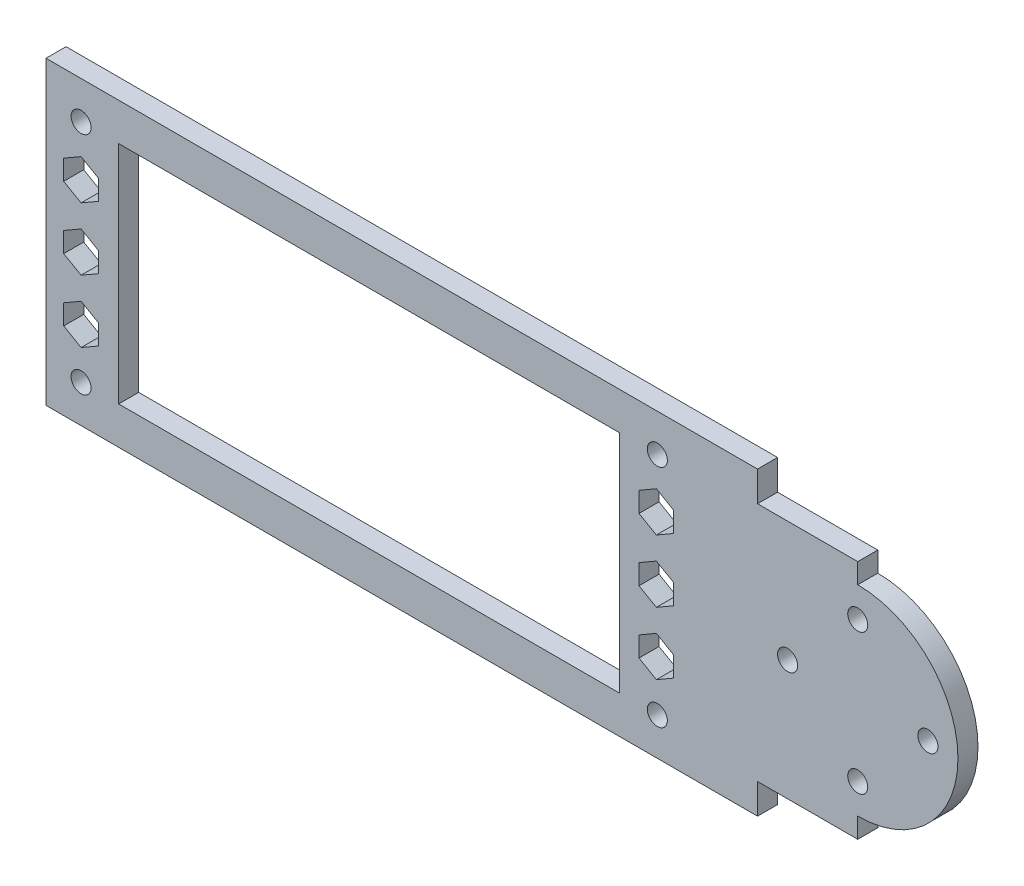
SolidWorks part; units mm, degrees
ref_plane "Front Plane" through (0, 0, 0) normal (0, 0, 1) x (1, 0, 0)
ref_plane "Top Plane" through (0, 0, 0) normal (0, 1, 0) x (1, 0, 0)
ref_plane "Right Plane" through (0, 0, 0) normal (1, 0, 0) x (0, 0, -1)
sketch "Sketch1" plane through (0, 0, 0) normal (0, 0, 1) x (1, 0, 0)
  line L0 (0, 10) -> (0, 12)
  line L1 (-10, 15) -> (-81, 15)
  line L2 (-81, 15) -> (-81, -15)
  line L3 (-81, -15) -> (-10, -15)
  line L4 (0, -12) -> (0, -10)
  line L5 (-10, 15) -> (-10, 12)
  line L6 (-10, 12) -> (0, 12)
  line L7 (-10, -15) -> (-10, -12)
  line L8 (-10, -12) -> (0, -12)
  line L10 (-73.75, 11.25) -> (-23.75, 11.25)
  line L11 (-73.75, 11.25) -> (-73.75, -11.25)
  line L12 (-73.75, -11.25) -> (-23.75, -11.25)
  line L13 (-23.75, 11.25) -> (-23.75, -11.25)
  line L14 (-73.75, 11.25) -> (-23.75, -11.25) construction
  line L15 (-73.75, -11.25) -> (-23.75, 11.25) construction
  line L16 (-20.0964, 8.25) -> (-21.8284, 7.25)
  line L17 (-21.8284, 7.25) -> (-21.8284, 5.25)
  line L18 (-21.8284, 5.25) -> (-20.0964, 4.25)
  line L19 (-20.0964, 4.25) -> (-18.3643, 5.25)
  line L20 (-18.3643, 5.25) -> (-18.3643, 7.25)
  line L21 (-18.3643, 7.25) -> (-20.0964, 8.25)
  line L22 (-20.0964, -8.25) -> (-18.3643, -7.25)
  line L23 (-18.3643, -7.25) -> (-18.3643, -5.25)
  line L24 (-18.3643, -5.25) -> (-20.0964, -4.25)
  line L25 (-20.0964, -4.25) -> (-21.8284, -5.25)
  line L26 (-21.8284, -5.25) -> (-21.8284, -7.25)
  line L27 (-21.8284, -7.25) -> (-20.0964, -8.25)
  line L28 (-20.0964, -2) -> (-18.3643, -1)
  line L29 (-18.3643, -1) -> (-18.3643, 1)
  line L30 (-18.3643, 1) -> (-20.0964, 2)
  line L31 (-20.0964, 2) -> (-21.8284, 1)
  line L32 (-21.8284, 1) -> (-21.8284, -1)
  line L33 (-21.8284, -1) -> (-20.0964, -2)
  line L34 (-77.5, 4.25) -> (-75.7679, 5.25)
  line L35 (-75.7679, 5.25) -> (-75.7679, 7.25)
  line L36 (-75.7679, 7.25) -> (-77.5, 8.25)
  line L37 (-77.5, 8.25) -> (-79.2321, 7.25)
  line L38 (-79.2321, 7.25) -> (-79.2321, 5.25)
  line L39 (-79.2321, 5.25) -> (-77.5, 4.25)
  line L40 (-77.5, -8.25) -> (-75.7679, -7.25)
  line L41 (-75.7679, -7.25) -> (-75.7679, -5.25)
  line L42 (-75.7679, -5.25) -> (-77.5, -4.25)
  line L43 (-77.5, -4.25) -> (-79.2321, -5.25)
  line L44 (-79.2321, -5.25) -> (-79.2321, -7.25)
  line L45 (-79.2321, -7.25) -> (-77.5, -8.25)
  line L46 (-77.5, -2) -> (-75.7679, -1)
  line L47 (-75.7679, -1) -> (-75.7679, 1)
  line L48 (-75.7679, 1) -> (-77.5, 2)
  line L49 (-77.5, 2) -> (-79.2321, 1)
  line L50 (-79.2321, 1) -> (-79.2321, -1)
  line L51 (-79.2321, -1) -> (-77.5, -2)
  arc A0 (0, -10) -> (0, 10) centre (0, 0) ccw
  circle A1 centre (0, 7) radius 1
  circle A2 centre (7, 0) radius 1
  circle A3 centre (0, -7) radius 1
  circle A4 centre (-7, 0) radius 1
  circle A7 centre (-20, 11.25) radius 1
  circle A8 centre (-20, -11.25) radius 1
  circle A13 centre (-77.5, 11.25) radius 1
  circle A14 centre (-77.5, -11.25) radius 1
  circle A15 centre (-20.0964, 6.25) radius 1.7321 construction
  circle A16 centre (-20.0964, -6.25) radius 1.7321 construction
  circle A17 centre (-20.0964, 0) radius 1.7321 construction
  circle A18 centre (-77.5, 6.25) radius 1.7321 construction
  circle A19 centre (-77.5, -6.25) radius 1.7321 construction
  circle A20 centre (-77.5, 0) radius 1.7321 construction
  point P14 (0, 0)
  point P17 (-48.75, 0)
  point P75 (0, 0)
  point P83 (0, 0)
  point P84 (0, 0)
  point P85 (0, 0)
  point P86 (0, 0)
  dimension "D1" = 20
  dimension "D2" = 7
  dimension "D10" = 22.5
  dimension "D11" = 2
  dimension "D12" = 2
  dimension "D13" = 3.75
  dimension "D14" = 2
  dimension "D15" = 2
  dimension "D4" = 2
  dimension "D5" = 3
  dimension "D6" = 3
  dimension "D7" = 2
  dimension "D8" = 10
  dimension "D9" = 10
  dimension "D16" = 57.5
  dimension "D17" = 71
  dimension "D18" = 50
  dimension "D19" = 22.5
  dimension "D20" = 3.75
  dimension "D21" = 2
  dimension "D22" = 2
  dimension "D23" = 2
  dimension "D24" = 2
  dimension "D25" = 2
  dimension "D26" = 2
  dimension "D27" = 5
  dimension "D28" = 5
  dimension "D29" = 5
  dimension "D30" = 5
  dimension "D31" = 6.25
  dimension "D32" = 6.25
  dimension "D33" = 6.25
  dimension "D3" = 4
extrude "Boss-Extrude1" add sketch "Sketch1" along normal blind 2
